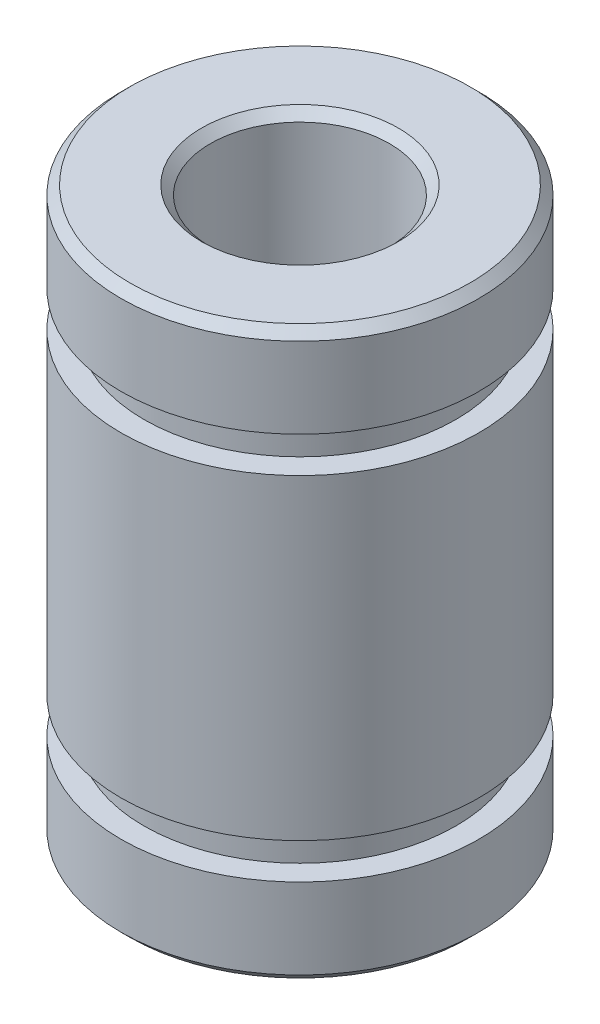
SolidWorks part; units mm, degrees
ref_plane "Front Plane" through (0, 0, 0) normal (0, 0, 1) x (1, 0, 0)
ref_plane "Top Plane" through (0, 0, 0) normal (0, 1, 0) x (1, 0, 0)
ref_plane "Right Plane" through (0, 0, 0) normal (1, 0, 0) x (0, 0, -1)
sketch "Sketch1" plane through (0, 0, 0) normal (0, 1, 0) x (1, 0, 0)
  circle A0 centre (0, 0) radius 6
  circle A1 centre (0, 0) radius 3
  dimension "D1" = 12
  dimension "D2" = 6
extrude "Boss-Extrude1" add sketch "Sketch1" along normal mid plane 19
sketch "Sketch2" plane through (0, 0, 0) normal (1, 0, 0) x (0, 0, -1)
  line L2 (0, 9.5) -> (0, -9.5) construction
  line L3 (3, 9.5) -> (-3, 9.5) construction
  line L4 (-6, -9.5) -> (6, -9.5) construction
  line L5 (6, -9.5) -> (6, 9.5) construction
  line L6 (6, 6.5) -> (5.23, 6.5)
  line L7 (6, 6.5) -> (6, 5.3)
  line L8 (6, 5.3) -> (5.23, 5.3)
  line L9 (5.23, 6.5) -> (5.23, 5.3)
  line L10 (0, 0) -> (6, 0) construction
  line L11 (6, -6.5) -> (5.23, -6.5)
  line L12 (6, -6.5) -> (6, -5.3)
  line L13 (6, -5.3) -> (5.23, -5.3)
  line L14 (5.23, -6.5) -> (5.23, -5.3)
  line L15 (6, 9.5) -> (-6, 9.5) construction
  dimension "D1" = 1.2
  dimension "D2" = 0.77
  dimension "D3" = 3
revolve "Cut-Revolve1" cut sketch "Sketch2" angle 360 about L2
chamfer "Chamfer1" distance 0.3 angle 45 4 edges at (0, -9.5, 3) (0, -9.5, 6) (0, 9.5, 3) (0, 9.5, 6)
